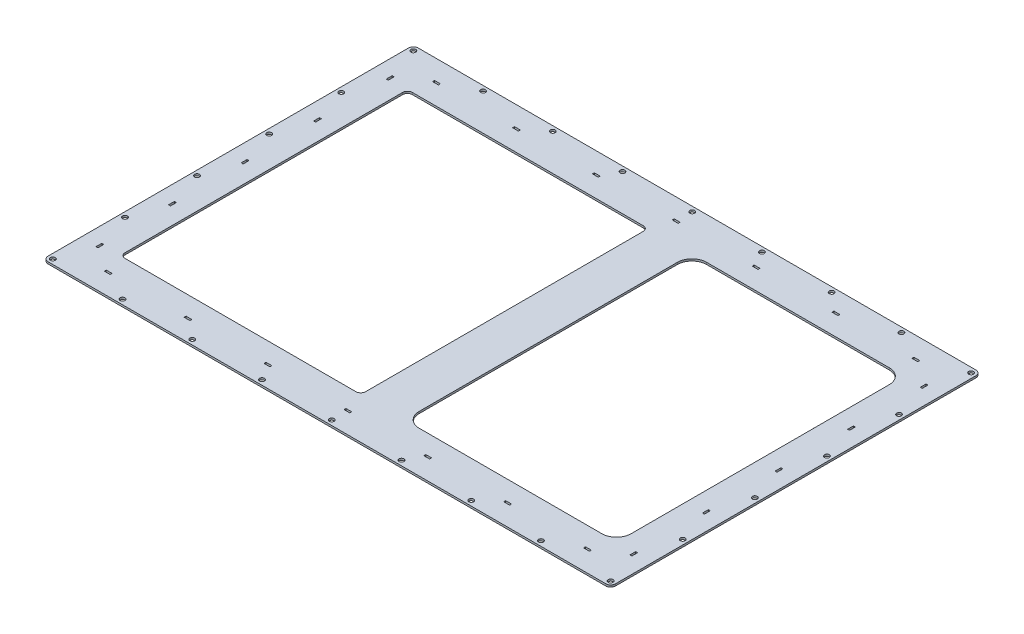
SolidWorks part; units mm, degrees
ref_plane "Спереди" through (0, 0, 0) normal (0, 0, 1) x (1, 0, 0)
ref_plane "Сверху" through (0, 0, 0) normal (0, 1, 0) x (1, 0, 0)
ref_plane "Справа" through (0, 0, 0) normal (1, 0, 0) x (0, 0, -1)
sketch "Эскиз1" plane through (0, 0, 0) normal (0, 1, 0) x (1, 0, 0)
  line L1 (-582.5, -380) -> (582.5, -380)
  line L2 (-582.5, -380) -> (-582.5, 380)
  line L3 (-582.5, 380) -> (582.5, 380)
  line L4 (582.5, -380) -> (582.5, 380)
  line L5 (0, 380) -> (0, -380) construction
  line L6 (-582.5, 0) -> (582.5, 0) construction
  line L7 (-509.5, 295) -> (-15.5, 295)
  line L8 (-509.5, 295) -> (-509.5, -295)
  line L9 (-509.5, -295) -> (-15.5, -295)
  line L10 (-15.5, 295) -> (-15.5, -295)
  line L11 (74.5, 295) -> (509.5, 295)
  line L12 (74.5, 295) -> (74.5, -295)
  line L13 (74.5, -295) -> (509.5, -295)
  line L14 (509.5, 295) -> (509.5, -295)
  point P0 (0, 0)
  dimension "D1" = 1165
  dimension "D2" = 760
  dimension "D3" = 73
  dimension "D4" = 85
  dimension "D5" = 85
  dimension "D6" = 494
  dimension "D7" = 73
  dimension "D8" = 435
extrude "Бобышка-Вытянуть1" add sketch "Эскиз1" along normal mid plane 4
fillet "Скругление1" radius 10 8 edges at (582.5, 0, 380) (-582.5, 0, 380) (582.5, 0, -380) (-582.5, 0, -380) (-15.5, 0, 295) (-509.5, 0, 295) (-15.5, 0, -295) (-509.5, 0, -295)
fillet "Скругление2" radius 30 4 edges at (74.5, 0, 295) (509.5, 0, 295) (509.5, 0, -295) (74.5, 0, -295)
sketch "Эскиз2" plane through (0, 2, 0) normal (0, 1, 0) x (1, 0, 0)
  circle A0 centre (-572.5, -370) radius 5
  arc A1 (-582.5, -370) -> (-572.5, -380) centre (-572.5, -370) ccw construction
  circle A2 centre (-572.5, 370) radius 5 construction
  arc A3 (-572.5, 380) -> (-582.5, 370) centre (-572.5, 370) ccw construction
  circle A4 centre (572.5, -370) radius 5 construction
  arc A5 (572.5, -380) -> (582.5, -370) centre (572.5, -370) ccw construction
  point P11 (-572.5, 370)
  point P17 (572.5, -370)
  dimension "D1" = 10
extrude "Вырез-Вытянуть1" cut sketch "Эскиз2" against normal through all
ref_plane "Плоскость1" through (29.5, 0, 0) normal (-1, 0, 0) x (0, 0, 1)
pattern_linear "Линейный массив1" count 6 spacing 148 along (0, 0, -1) count 9 spacing 143.125 along (1, 0, 0) skipping (1, 1), (1, 2), (1, 3), (1, 4), (1, 5), (1, 6), (1, 7), (2, 1), (2, 2), (2, 3), (2, 4), (2, 5), (2, 6), (2, 7), (3, 1), (3, 2), (3, 3), (3, 4), (3, 5), (3, 6), (3, 7), (4, 1), (4, 2), (4, 3), (4, 4) of "Вырез-Вытянуть1"
sketch "Эскиз3" plane through (0, 2, 0) normal (0, 1, 0) x (1, 0, 0)
  line L4 (486, 335) -> (498, 335)
  line L5 (486, 339) -> (486, 335)
  line L6 (498, 339) -> (486, 339)
  line L7 (498, 335) -> (498, 339)
  line L8 (486, 335) -> (498, 335)
  line L9 (486, 339) -> (486, 335)
  line L10 (498, 339) -> (486, 339)
  line L11 (498, 335) -> (498, 339)
  line L12 (322, 335) -> (334, 335)
  line L13 (322, 339) -> (322, 335)
  line L14 (334, 339) -> (322, 339)
  line L15 (334, 335) -> (334, 339)
  line L16 (322, 335) -> (334, 335)
  line L17 (322, 339) -> (322, 335)
  line L18 (334, 339) -> (322, 339)
  line L19 (334, 335) -> (334, 339)
  line L20 (6, 339) -> (-6, 339)
  line L21 (6, 335) -> (6, 339)
  line L22 (-6, 335) -> (6, 335)
  line L23 (-6, 339) -> (-6, 335)
  line L24 (6, 339) -> (-6, 339)
  line L25 (6, 335) -> (6, 339)
  line L26 (-6, 335) -> (6, 335)
  line L27 (-6, 339) -> (-6, 335)
  line L28 (170, 339) -> (158, 339)
  line L29 (158, 339) -> (158, 335)
  line L30 (158, 335) -> (170, 335)
  line L31 (170, 335) -> (170, 339)
  line L32 (170, 339) -> (158, 339)
  line L33 (158, 339) -> (158, 335)
  line L34 (158, 335) -> (170, 335)
  line L35 (170, 335) -> (170, 339)
  line L36 (-498, 335) -> (-486, 335)
  line L37 (-498, 339) -> (-498, 335)
  line L38 (-486, 339) -> (-498, 339)
  line L39 (-486, 335) -> (-486, 339)
  line L40 (-498, 335) -> (-486, 335)
  line L41 (-498, 339) -> (-498, 335)
  line L42 (-486, 339) -> (-498, 339)
  line L43 (-486, 335) -> (-486, 339)
  line L44 (-170, 335) -> (-158, 335)
  line L45 (-170, 339) -> (-170, 335)
  line L46 (-158, 339) -> (-170, 339)
  line L47 (-158, 335) -> (-158, 339)
  line L48 (-170, 335) -> (-158, 335)
  line L49 (-170, 339) -> (-170, 335)
  line L50 (-158, 339) -> (-170, 339)
  line L51 (-158, 335) -> (-158, 339)
  line L52 (-334, 335) -> (-322, 335)
  line L53 (-334, 339) -> (-334, 335)
  line L54 (-322, 339) -> (-334, 339)
  line L55 (-322, 335) -> (-322, 339)
  line L56 (-334, 335) -> (-322, 335)
  line L57 (-334, 339) -> (-334, 335)
  line L58 (-322, 339) -> (-334, 339)
  line L59 (-322, 335) -> (-322, 339)
  line L60 (486, -339) -> (498, -339)
  line L61 (486, -335) -> (486, -339)
  line L62 (498, -335) -> (486, -335)
  line L63 (498, -339) -> (498, -335)
  line L64 (486, -339) -> (498, -339)
  line L65 (486, -335) -> (486, -339)
  line L66 (498, -335) -> (486, -335)
  line L67 (498, -339) -> (498, -335)
  line L68 (322, -339) -> (334, -339)
  line L69 (322, -335) -> (322, -339)
  line L70 (334, -335) -> (322, -335)
  line L71 (334, -339) -> (334, -335)
  line L72 (322, -339) -> (334, -339)
  line L73 (322, -335) -> (322, -339)
  line L74 (334, -335) -> (322, -335)
  line L75 (334, -339) -> (334, -335)
  line L76 (6, -335) -> (-6, -335)
  line L77 (6, -339) -> (6, -335)
  line L78 (-6, -339) -> (6, -339)
  line L79 (-6, -335) -> (-6, -339)
  line L80 (6, -335) -> (-6, -335)
  line L81 (6, -339) -> (6, -335)
  line L82 (-6, -339) -> (6, -339)
  line L83 (-6, -335) -> (-6, -339)
  line L84 (170, -335) -> (158, -335)
  line L85 (158, -335) -> (158, -339)
  line L86 (158, -339) -> (170, -339)
  line L87 (170, -339) -> (170, -335)
  line L88 (170, -335) -> (158, -335)
  line L89 (158, -335) -> (158, -339)
  line L90 (158, -339) -> (170, -339)
  line L91 (170, -339) -> (170, -335)
  line L92 (-498, -339) -> (-486, -339)
  line L93 (-498, -335) -> (-498, -339)
  line L94 (-486, -335) -> (-498, -335)
  line L95 (-486, -339) -> (-486, -335)
  line L96 (-498, -339) -> (-486, -339)
  line L97 (-498, -335) -> (-498, -339)
  line L98 (-486, -335) -> (-498, -335)
  line L99 (-486, -339) -> (-486, -335)
  line L100 (-170, -339) -> (-158, -339)
  line L101 (-170, -335) -> (-170, -339)
  line L102 (-158, -335) -> (-170, -335)
  line L103 (-158, -339) -> (-158, -335)
  line L104 (-170, -339) -> (-158, -339)
  line L105 (-170, -335) -> (-170, -339)
  line L106 (-158, -335) -> (-170, -335)
  line L107 (-158, -339) -> (-158, -335)
  line L108 (-334, -339) -> (-322, -339)
  line L109 (-334, -335) -> (-334, -339)
  line L110 (-322, -335) -> (-334, -335)
  line L111 (-322, -339) -> (-322, -335)
  line L112 (-334, -339) -> (-322, -339)
  line L113 (-334, -335) -> (-334, -339)
  line L114 (-322, -335) -> (-334, -335)
  line L115 (-322, -339) -> (-322, -335)
  line L116 (-546, 143) -> (-546, 155)
  line L117 (-550, 143) -> (-546, 143)
  line L118 (-550, 155) -> (-550, 143)
  line L119 (-546, 155) -> (-550, 155)
  line L120 (-546, 143) -> (-546, 155)
  line L121 (-550, 143) -> (-546, 143)
  line L122 (-550, 155) -> (-550, 143)
  line L123 (-546, 155) -> (-550, 155)
  line L124 (-550, 304) -> (-550, 292)
  line L125 (-546, 304) -> (-550, 304)
  line L126 (-546, 292) -> (-546, 304)
  line L127 (-550, 292) -> (-546, 292)
  line L128 (-550, 304) -> (-550, 292)
  line L129 (-546, 304) -> (-550, 304)
  line L130 (-546, 292) -> (-546, 304)
  line L131 (-550, 292) -> (-546, 292)
  line L132 (-550, -143) -> (-550, -155)
  line L133 (-546, -143) -> (-550, -143)
  line L134 (-546, -155) -> (-546, -143)
  line L135 (-550, -155) -> (-546, -155)
  line L136 (-550, -143) -> (-550, -155)
  line L137 (-546, -143) -> (-550, -143)
  line L138 (-546, -155) -> (-546, -143)
  line L139 (-550, -155) -> (-546, -155)
  line L140 (-550, 6) -> (-550, -6)
  line L141 (-546, 6) -> (-550, 6)
  line L142 (-546, -6) -> (-546, 6)
  line L143 (-550, -6) -> (-546, -6)
  line L144 (-550, 6) -> (-550, -6)
  line L145 (-546, 6) -> (-550, 6)
  line L146 (-546, -6) -> (-546, 6)
  line L147 (-550, -6) -> (-546, -6)
  line L148 (-550, -292) -> (-550, -304)
  line L149 (-546, -292) -> (-550, -292)
  line L150 (-546, -304) -> (-546, -292)
  line L151 (-550, -304) -> (-546, -304)
  line L152 (-550, -292) -> (-550, -304)
  line L153 (-546, -292) -> (-550, -292)
  line L154 (-546, -304) -> (-546, -292)
  line L155 (-550, -304) -> (-546, -304)
  line L176 (546, -143) -> (546, -155)
  line L177 (550, -143) -> (546, -143)
  line L178 (550, -155) -> (550, -143)
  line L179 (546, -155) -> (550, -155)
  line L180 (546, -143) -> (546, -155)
  line L181 (550, -143) -> (546, -143)
  line L182 (550, -155) -> (550, -143)
  line L183 (546, -155) -> (550, -155)
  line L184 (550, -304) -> (550, -292)
  line L185 (546, -304) -> (550, -304)
  line L186 (546, -292) -> (546, -304)
  line L187 (550, -292) -> (546, -292)
  line L188 (550, -304) -> (550, -292)
  line L189 (546, -304) -> (550, -304)
  line L190 (546, -292) -> (546, -304)
  line L191 (550, -292) -> (546, -292)
  line L192 (550, 143) -> (550, 155)
  line L193 (546, 143) -> (550, 143)
  line L194 (546, 155) -> (546, 143)
  line L195 (550, 155) -> (546, 155)
  line L196 (550, 143) -> (550, 155)
  line L197 (546, 143) -> (550, 143)
  line L198 (546, 155) -> (546, 143)
  line L199 (550, 155) -> (546, 155)
  line L200 (550, -6) -> (550, 6)
  line L201 (546, -6) -> (550, -6)
  line L202 (546, 6) -> (546, -6)
  line L203 (550, 6) -> (546, 6)
  line L204 (550, -6) -> (550, 6)
  line L205 (546, -6) -> (550, -6)
  line L206 (546, 6) -> (546, -6)
  line L207 (550, 6) -> (546, 6)
  line L208 (550, 292) -> (550, 304)
  line L209 (546, 292) -> (550, 292)
  line L210 (546, 304) -> (546, 292)
  line L211 (550, 304) -> (546, 304)
  line L212 (550, 292) -> (550, 304)
  line L213 (546, 292) -> (550, 292)
  line L214 (546, 304) -> (546, 292)
  line L215 (550, 304) -> (546, 304)
  dimension "D1" = 0
  dimension "D2" = 0
  dimension "D3" = 0
  dimension "D4" = 0
  dimension "D5" = 0
  dimension "D6" = 0
  dimension "D7" = 0
  dimension "D8" = 0
  dimension "D9" = 0
  dimension "D10" = 0
  dimension "D11" = 0
  dimension "D12" = 0
  dimension "D13" = 0
  dimension "D14" = 0
  dimension "D15" = 0
  dimension "D16" = 0
  dimension "D17" = 0
  dimension "D18" = 0
  dimension "D19" = 0
  dimension "D20" = 0
  dimension "D21" = 0
  dimension "D22" = 0
  dimension "D23" = 0
  dimension "D24" = 0
extrude "Вырез-Вытянуть2" cut sketch "Эскиз3" against normal through all
